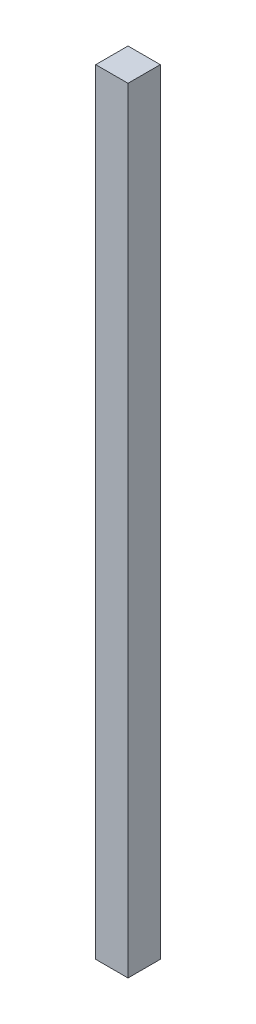
SolidWorks part; units mm, degrees
ref_plane "Front Plane" through (0, 0, 0) normal (0, 0, 1) x (1, 0, 0)
ref_plane "Top Plane" through (0, 0, 0) normal (0, 1, 0) x (1, 0, 0)
ref_plane "Right Plane" through (0, 0, 0) normal (1, 0, 0) x (0, 0, -1)
sketch "Sketch1" plane through (0, 0, 0) normal (0, 1, 0) x (1, 0, 0)
  line L1 (-50.8, -50.8) -> (50.8, -50.8)
  line L2 (-50.8, -50.8) -> (-50.8, 50.8)
  line L3 (-50.8, 50.8) -> (50.8, 50.8)
  line L4 (50.8, -50.8) -> (50.8, 50.8)
  line L5 (-50.8, -50.8) -> (50.8, 50.8) construction
  line L6 (-50.8, 50.8) -> (50.8, -50.8) construction
  point P0 (0, 0)
  dimension "D1" = 101.6
  dimension "D2" = 101.6
extrude "Boss-Extrude1" add sketch "Sketch1" along normal blind 2438.4
